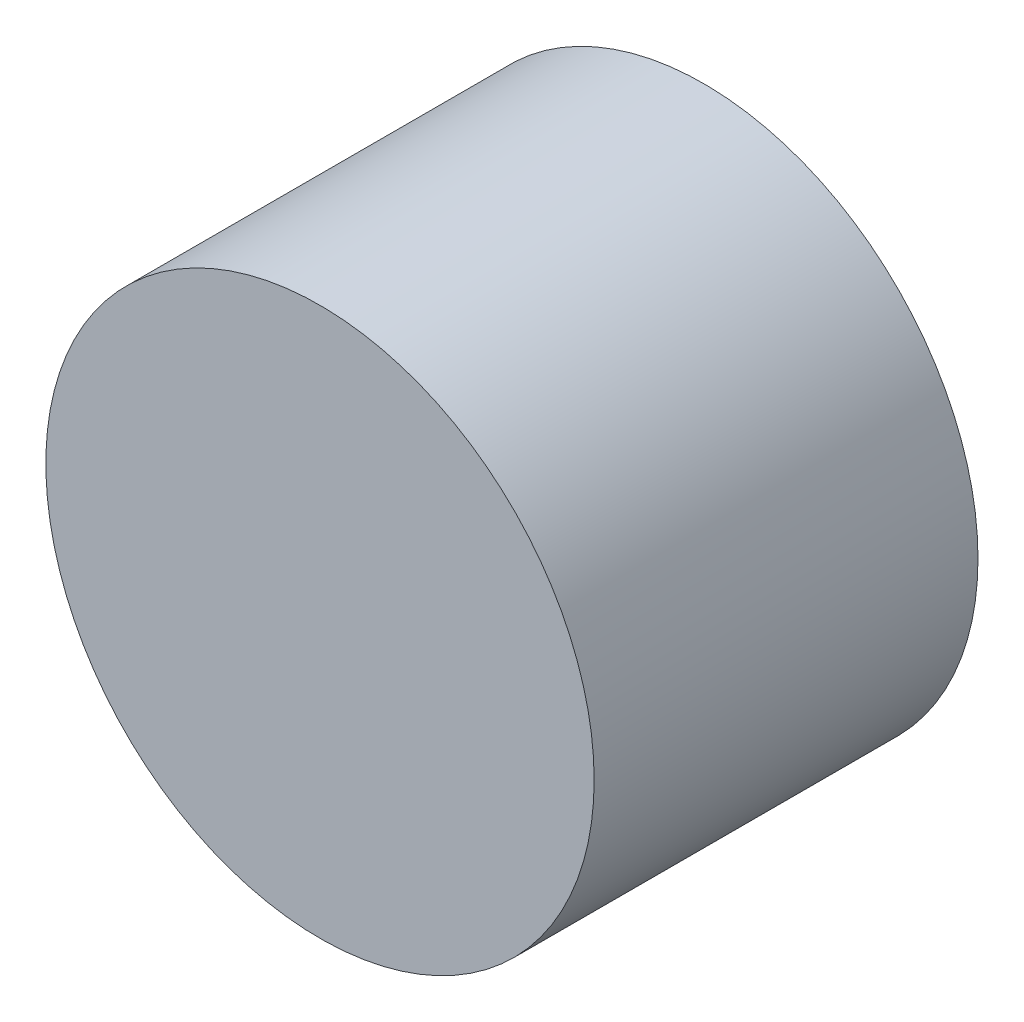
SolidWorks part; units mm, degrees
ref_plane "Alzado" through (0, 0, 0) normal (0, 0, 1) x (1, 0, 0)
ref_plane "Planta" through (0, 0, 0) normal (0, 1, 0) x (1, 0, 0)
ref_plane "Vista lateral" through (0, 0, 0) normal (1, 0, 0) x (0, 0, -1)
sketch "Croquis1" plane through (0, 0, 0) normal (0, 0, 1) x (1, 0, 0)
  circle A0 centre (-4.9763, -25.8) radius 15
  dimension "D1" = 30
extrude "Saliente-Extruir1" add sketch "Croquis1" along normal blind 21
